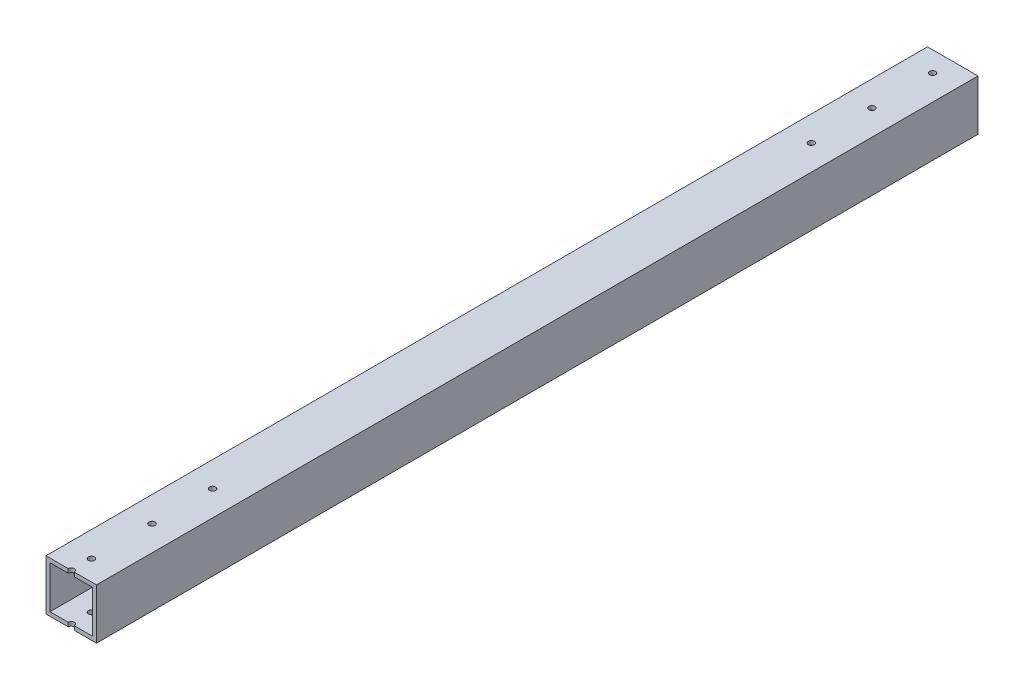
SolidWorks part; units mm, degrees
material "6061-T4 (SS)"
ref_plane "Front Plane" through (0, 0, 0) normal (0, 0, 1) x (1, 0, 0)
ref_plane "Top Plane" through (0, 0, 0) normal (0, 1, 0) x (1, 0, 0)
ref_plane "Right Plane" through (0, 0, 0) normal (1, 0, 0) x (0, 0, -1)
sketch "Sketch1" plane through (0, 0, 0) normal (0, 0, 1) x (1, 0, 0)
  line L0 (-12.5, -12.5) -> (12.5, -12.5)
  line L1 (-12.5, -12.5) -> (-12.5, 12.5)
  line L2 (12.5, -12.5) -> (12.5, 12.5)
  line L3 (-12.5, 12.5) -> (12.5, 12.5)
  line L4 (-12.5, -12.5) -> (12.5, 12.5) construction
  line L5 (12.5, -12.5) -> (-12.5, 12.5) construction
  line L6 (-10.5, 10.5) -> (10.5, 10.5)
  line L7 (10.5, -10.5) -> (10.5, 10.5)
  line L8 (-10.5, -10.5) -> (10.5, -10.5)
  line L9 (-10.5, -10.5) -> (-10.5, 10.5)
  point P1 (0, 0)
  dimension "D1" = 25
  dimension "D2" = 25
  dimension "D3" = 2
extrude "Boss-Extrude1" add sketch "Sketch1" against normal blind 436.5
sketch "Sketch2" plane through (0, 12.5, 0) normal (0, 1, 0) x (1, 0, 0)
  line L0 (0, 436.5) -> (0, 426.5)
  line L1 (12.5, 436.5) -> (-12.5, 436.5) construction
  line L2 (0, 426.5) -> (0, 396.5)
  line L3 (0, 396.5) -> (0, 366.5)
  circle A0 centre (0, 366.5) radius 1.5
  circle A1 centre (0, 396.5) radius 1.5
  circle A2 centre (0, 426.5) radius 1.5
  dimension "D4" = 3
  dimension "D5" = 3
  dimension "D6" = 3
  dimension "D1" = 10
  dimension "D2" = 30
  dimension "D3" = 30
extrude "Cut-Extrude1" cut sketch "Sketch2" against normal through all contours A0 | A1 | A2
ref_plane "Plane1" through (0, 0, -218.25) normal (0, 0, 1) x (1, 0, 0)
sketch "Sketch3" plane through (0, 12.5, 0) normal (0, 1, 0) x (1, 0, 0)
  circle A0 centre (0, 0) radius 1.5
  dimension "D1" = 3
extrude "Cut-Extrude2" cut sketch "Sketch3" against normal blind 429
mirror "Mirror1" about plane through (0, 0, -218.25) normal (0, 0, 1) of "Cut-Extrude1"
